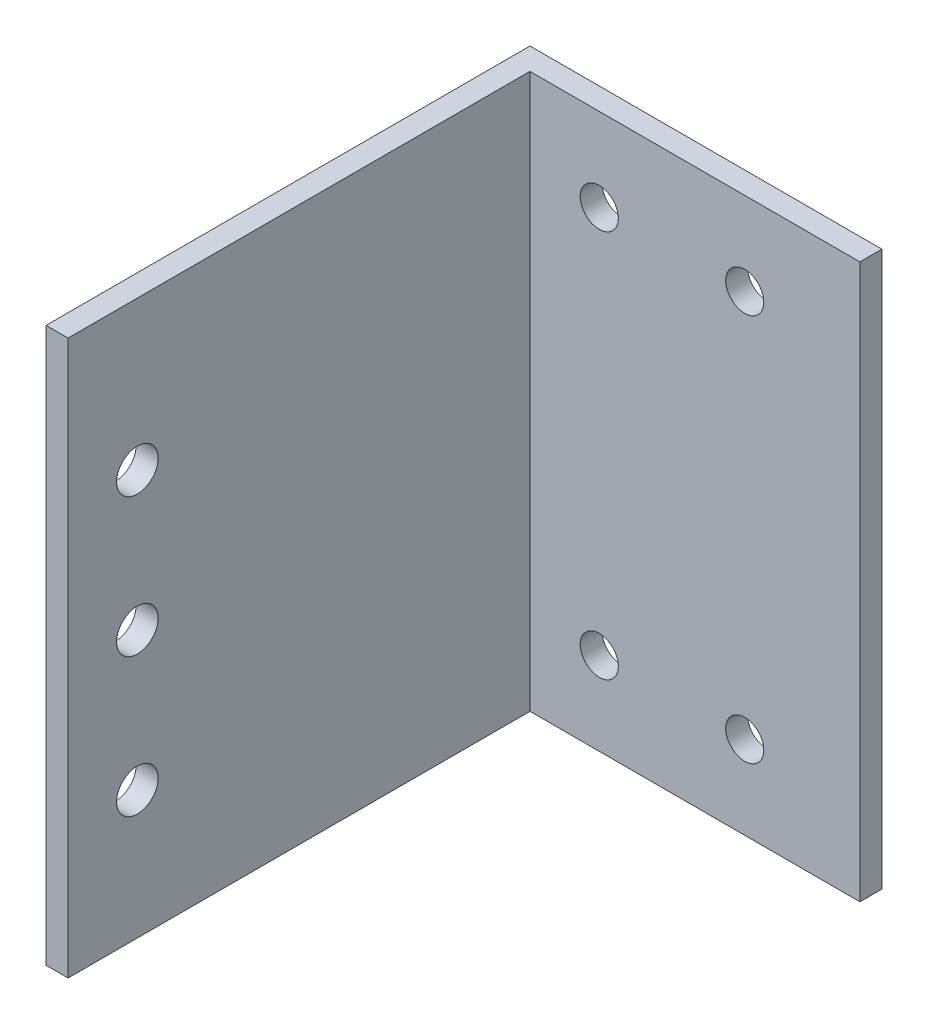
SolidWorks part; units mm, degrees
ref_plane "Front Plane" through (0, 0, 0) normal (0, 0, 1) x (1, 0, 0)
ref_plane "Top Plane" through (0, 0, 0) normal (0, 1, 0) x (1, 0, 0)
ref_plane "Right Plane" through (0, 0, 0) normal (1, 0, 0) x (0, 0, -1)
sketch "Croquis2" plane through (0, 0, 0) normal (0, 0, 1) x (1, 0, 0)
  line L1 (0, 0) -> (50.8, 0)
  line L2 (0, 0) -> (0, 80)
  line L3 (0, 80) -> (50.8, 80)
  line L4 (50.8, 0) -> (50.8, 80)
  dimension "D1" = 50.8
  dimension "D2" = 80
extrude "Saliente-Extruir1" add sketch "Croquis2" along normal blind 3.175
sketch "Croquis3" plane through (0, 0, 3.175) normal (0, 0, 1) x (1, 0, 0)
  line L0 (0, 0) -> (50.8, 0) construction
  line L1 (0, 80) -> (3.175, 80)
  line L2 (0, 80) -> (0, 0)
  line L3 (0, 0) -> (3.175, 0)
  line L4 (3.175, 80) -> (3.175, 0)
  dimension "D1" = 3.175
extrude "Saliente-Extruir2" add sketch "Croquis3" along normal blind 66.675
sketch "Croquis4" plane through (0, 0, 3.175) normal (0, 0, 1) x (1, 0, 0)
  line L0 (3.175, 0) -> (50.8, 0) construction
  line L1 (3.175, 0) -> (3.175, 80) construction
  line L2 (3.175, 0) -> (3.175, 80) construction
  circle A0 centre (13.175, 68) radius 2.75
  circle A1 centre (13.175, 12) radius 2.75
  circle A2 centre (34.175, 68) radius 2.75
  circle A3 centre (34.175, 12) radius 2.75
  dimension "D1" = 56
  dimension "D2" = 12
  dimension "D3" = 5.5
  dimension "D4" = 5.5
  dimension "D5" = 21
  dimension "D6" = 21
  dimension "D7" = 10
  dimension "D8" = 10
extrude "Cortar-Extruir1" cut sketch "Croquis4" against normal blind 47.625
sketch "Croquis5" plane through (3.175, 0, 0) normal (1, 0, 0) x (0, 0, -1)
  line L2 (-69.85, 0) -> (-3.175, 0) construction
  line L3 (-69.85, 0) -> (-69.85, 80) construction
  circle A2 centre (-59.85, 18.5) radius 3
  circle A3 centre (-59.85, 38.5) radius 3
  circle A4 centre (-59.85, 58.5) radius 3
  dimension "D1" = 3
  dimension "D2" = 10
  dimension "D3" = 18.5
extrude "Cortar-Extruir2" cut sketch "Croquis5" against normal blind 47.625
